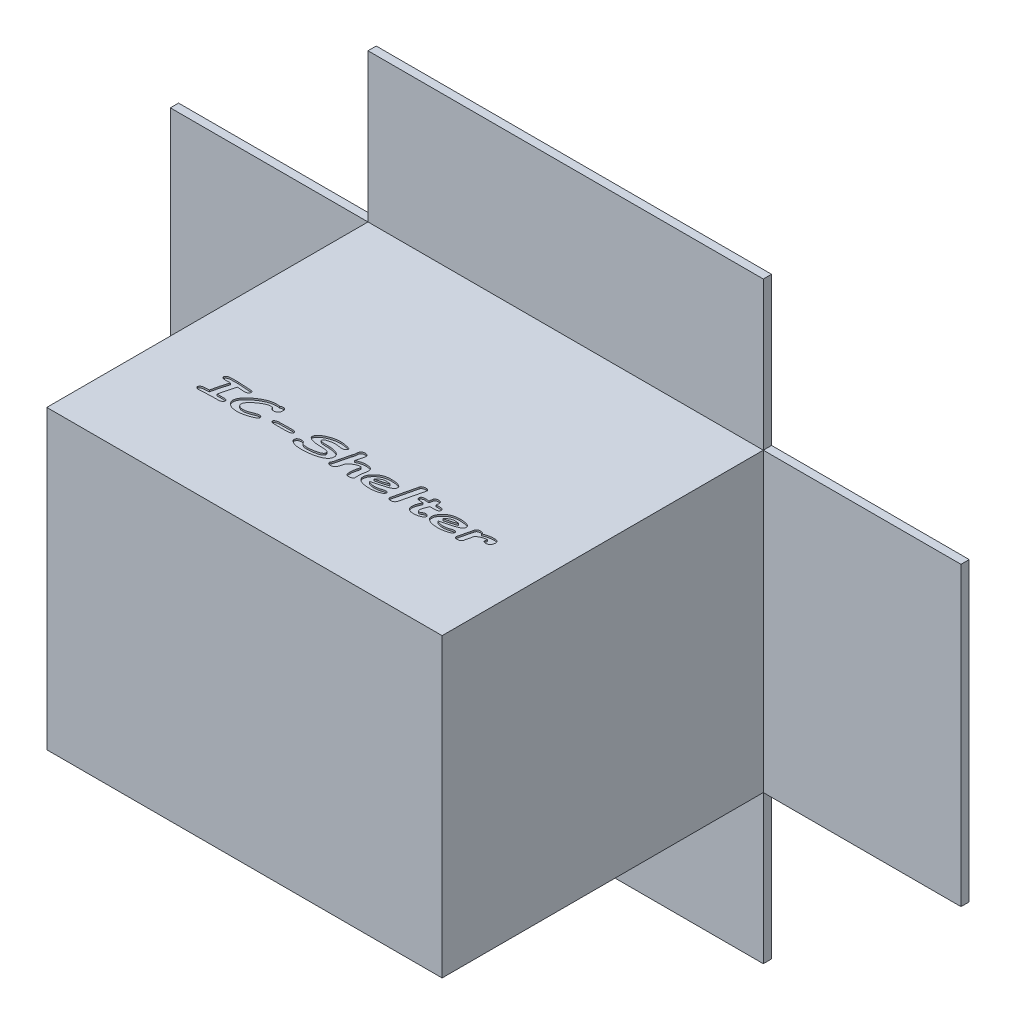
SolidWorks part; units mm, degrees
ref_plane "Alzado" through (0, 0, 0) normal (0, 0, 1) x (1, 0, 0)
ref_plane "Planta" through (0, 0, 0) normal (0, 1, 0) x (1, 0, 0)
ref_plane "Vista lateral" through (0, 0, 0) normal (1, 0, 0) x (0, 0, -1)
sketch "Croquis1" plane through (0, 0, 0) normal (0, 0, 1) x (1, 0, 0)
  line L1 (-60, -45) -> (60, -45)
  line L2 (-60, -45) -> (-60, 45)
  line L3 (-60, 45) -> (60, 45)
  line L4 (60, -45) -> (60, 45)
  line L5 (-60, -45) -> (60, 45) construction
  line L6 (-60, 45) -> (60, -45) construction
  point P0 (0, 0)
  dimension "D1" = 90
  dimension "D2" = 120
extrude "Saliente-Extruir1" add sketch "Croquis1" along normal blind 100
sketch "Croquis2" plane through (0, 0, 0) normal (0, 0, -1) x (-1, 0, 0)
  line L12 (-57.5, 42.5) -> (-57.5, -42.5)
  line L13 (-57.5, -42.5) -> (57.5, -42.5)
  line L14 (57.5, -42.5) -> (57.5, 42.5)
  line L15 (57.5, 42.5) -> (-57.5, 42.5)
  line L16 (-57.5, 42.5) -> (-57.5, -42.5)
  line L17 (-57.5, -42.5) -> (57.5, -42.5)
  line L18 (57.5, -42.5) -> (57.5, 42.5)
  line L19 (57.5, 42.5) -> (-57.5, 42.5)
  dimension "D1" = 2.5
extrude "Cortar-Extruir1" cut sketch "Croquis2" against normal blind 97.5
sketch "Croquis3" plane through (0, 0, 0) normal (0, 0, -1) x (-1, 0, 0)
  line L1 (-60, 45) -> (60, 45)
  line L2 (-60, 45) -> (-60, 90)
  line L3 (-60, 90) -> (60, 90)
  line L4 (60, 45) -> (60, 90)
  line L9 (-60, -45) -> (60, -45)
  line L10 (-60, -45) -> (-60, -90)
  line L11 (-60, -90) -> (60, -90)
  line L12 (60, -45) -> (60, -90)
  line L13 (-60, -45) -> (-120, -45)
  line L14 (-60, -45) -> (-60, 45)
  line L15 (-60, 45) -> (-120, 45)
  line L16 (-120, -45) -> (-120, 45)
  line L17 (60, 45) -> (120, 45)
  line L18 (60, 45) -> (60, -45)
  line L19 (60, -45) -> (120, -45)
  line L20 (120, 45) -> (120, -45)
  line L21 (-57.5, -42.5) -> (57.5, -42.5)
  line L22 (-57.5, -42.5) -> (-57.5, 42.5)
  line L23 (-57.5, 42.5) -> (57.5, 42.5)
  line L24 (57.5, -42.5) -> (57.5, 42.5)
  line L25 (-57.5, -42.5) -> (57.5, 42.5) construction
  line L26 (-57.5, 42.5) -> (57.5, -42.5) construction
  point P7 (0, 0)
  line M22 (-57.5, 42.5) -> (57.5, 42.5)
  line M23 (57.5, 42.5) -> (57.5, -42.5)
  line M24 (57.5, -42.5) -> (-57.5, -42.5)
  line M25 (-57.5, -42.5) -> (-57.5, 42.5)
  line M26 (-60, 45) -> (-60, -45)
  line M27 (-60, -45) -> (60, -45)
  line M28 (60, -45) -> (60, 45)
  line M29 (60, 45) -> (-60, 45)
  dimension "D1" = 60
  dimension "D2" = 60
  dimension "D3" = 45
  dimension "D4" = 45
extrude "Saliente-Extruir2" add sketch "Croquis3" against normal blind 2.5 contours L16 L13 L15 M26 | L4 L3 L2 M29 | M29 M26 M27 M28 M25 M22 M23 M24 | L20 L17 L19 M28 | L12 L10 L11 M27
sketch "Sketch1" plane through (0, 45, 0) normal (0, 1, 0) x (1, 0, 0)
  line L0 (-60, -72.0692) -> (60, -72.0692) construction
  line L1 (-60, -100) -> (-60, -2.5) construction
  line L2 (60, -100) -> (60, -2.5) construction
  text T0 "IC-Shelter" font "Comic Sans MS" height 8
extrude "Cut-Extrude1" cut sketch "Sketch1" against normal blind 0.5
